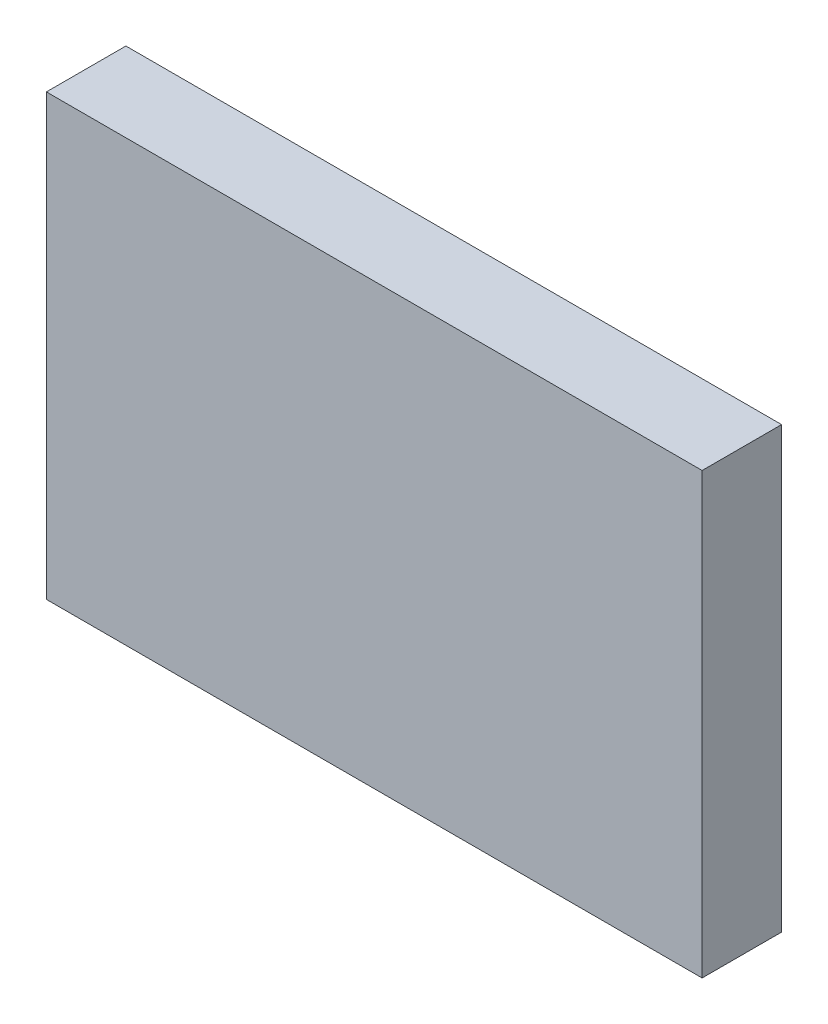
SolidWorks part; units mm, degrees
ref_plane "Plan de face" through (0, 0, 0) normal (0, 0, 1) x (1, 0, 0)
ref_plane "Plan de dessus" through (0, 0, 0) normal (0, 1, 0) x (1, 0, 0)
ref_plane "Plan de droite" through (0, 0, 0) normal (1, 0, 0) x (0, 0, -1)
sketch "Esquisse1" plane through (0, 0, 0) normal (0, 0, 1) x (1, 0, 0)
  line L1 (-41.25, -27.65) -> (41.25, -27.65)
  line L2 (-41.25, -27.65) -> (-41.25, 27.65)
  line L3 (-41.25, 27.65) -> (41.25, 27.65)
  line L4 (41.25, -27.65) -> (41.25, 27.65)
  line L5 (-41.25, -27.65) -> (41.25, 27.65) construction
  line L6 (-41.25, 27.65) -> (41.25, -27.65) construction
  point P0 (0, 0)
  dimension "D1" = 82.5
  dimension "D2" = 55.3
extrude "Boss.-Extru.1" add sketch "Esquisse1" along normal blind 10
